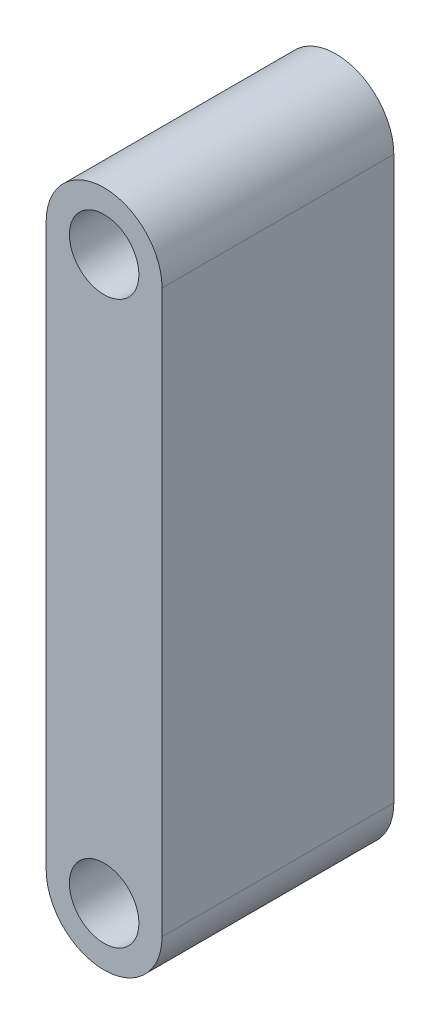
SolidWorks part; units mm, degrees
ref_plane "Piano frontale" through (0, 0, 0) normal (0, 0, 1) x (1, 0, 0)
ref_plane "Piano superiore" through (0, 0, 0) normal (0, 1, 0) x (1, 0, 0)
ref_plane "Piano destro" through (0, 0, 0) normal (1, 0, 0) x (0, 0, -1)
sketch "Schizzo2" plane through (0, 0, 0) normal (0, 0, 1) x (1, 0, 0)
  line L0 (0, 202.7564) -> (0, -39.6436) construction
  line L1 (25, 202.7564) -> (25, -39.6436)
  line L2 (-25, 202.7564) -> (-25, -39.6436)
  arc A0 (25, 202.7564) -> (-25, 202.7564) centre (0, 202.7564) ccw
  arc A1 (-25, -39.6436) -> (25, -39.6436) centre (0, -39.6436) ccw
  circle A2 centre (0, 202.7564) radius 15
  circle A3 centre (0, -39.6436) radius 15
  point P3 (0, 81.5564)
  dimension "D2" = 30
  dimension "D3" = 30
  dimension "D1" = 242.4
  dimension "D4" = 50
extrude "Estrusione-Estrusione1" add sketch "Schizzo2" along normal mid plane 100
